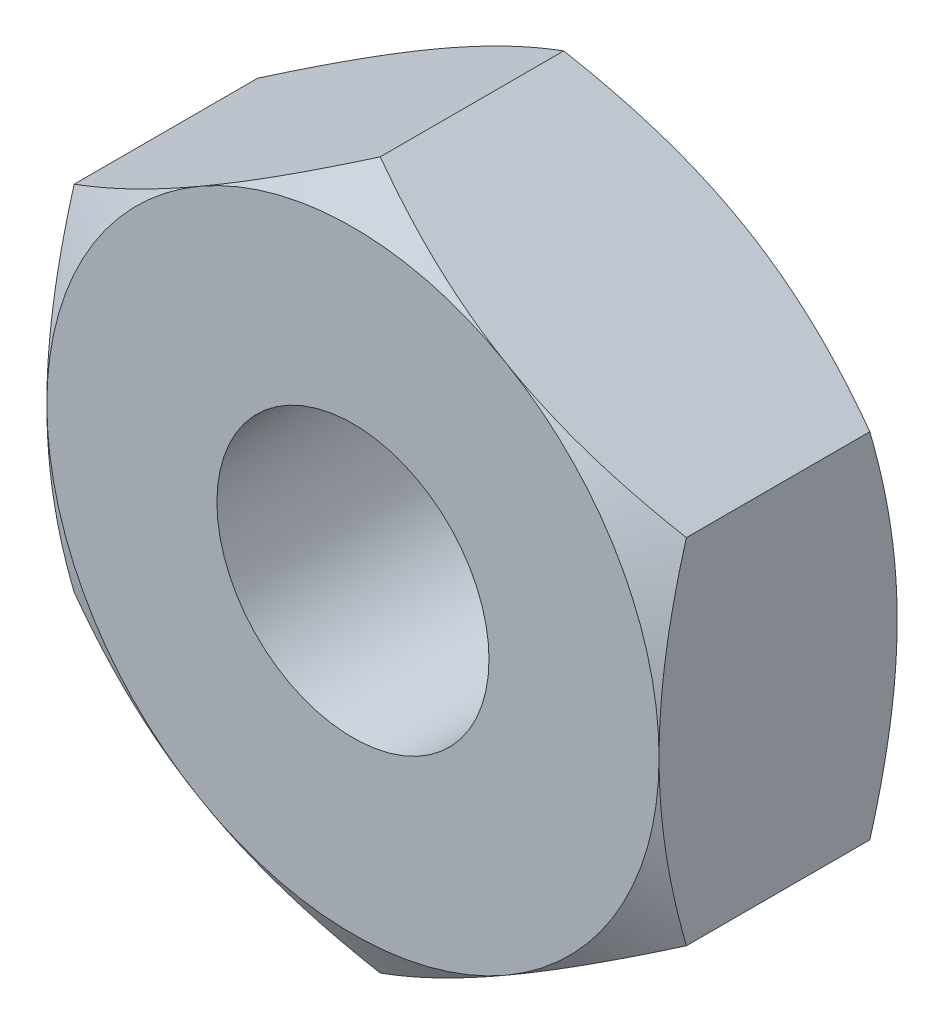
SolidWorks part; units mm, degrees
ref_plane "Front Plane" through (0, 0, 0) normal (0, 0, 1) x (1, 0, 0)
ref_plane "Top Plane" through (0, 0, 0) normal (0, 1, 0) x (1, 0, 0)
ref_plane "Right Plane" through (0, 0, 0) normal (1, 0, 0) x (0, 0, -1)
sketch "Sketch1" plane through (0, 0, 0) normal (0, 0, 1) x (1, 0, 0)
  line L1 (2.25, 1.299) -> (0, 2.5981)
  line L2 (0, 2.5981) -> (-2.25, 1.299)
  line L3 (-2.25, 1.299) -> (-2.25, -1.299)
  line L4 (-2.25, -1.299) -> (0, -2.5981)
  line L5 (0, -2.5981) -> (2.25, -1.299)
  line L6 (2.25, -1.299) -> (2.25, 1.299)
  circle A0 centre (0, 0) radius 1
  circle A1 centre (0, 0) radius 2.25 construction
  dimension "D1" = 4.5
  dimension "D2" = 2
extrude "Boss-Extrude1" add sketch "Sketch1" along normal blind 1.75
sketch "Sketch2" plane through (0, 0, 1.75) normal (0, 0, 1) x (1, 0, 0)
  circle A0 centre (0, 0) radius 2.25 construction
  circle A1 centre (0, 0) radius 2.25
  circle A2 centre (0, 0) radius 3.7984
extrude "Cut-Extrude1" cut sketch "Sketch2" against normal blind 2 draft 60
sketch "Sketch3" plane through (0, 0, 0) normal (0, 0, -1) x (-1, 0, 0)
  circle A0 centre (0, 0) radius 2.25 construction
  circle A1 centre (0, 0) radius 2.25
  circle A2 centre (0, 0) radius 3.5136
extrude "Cut-Extrude2" cut sketch "Sketch3" against normal blind 2 draft 60
scale "Scale1" scale about centroid uniform scaling yes scale factor 18
